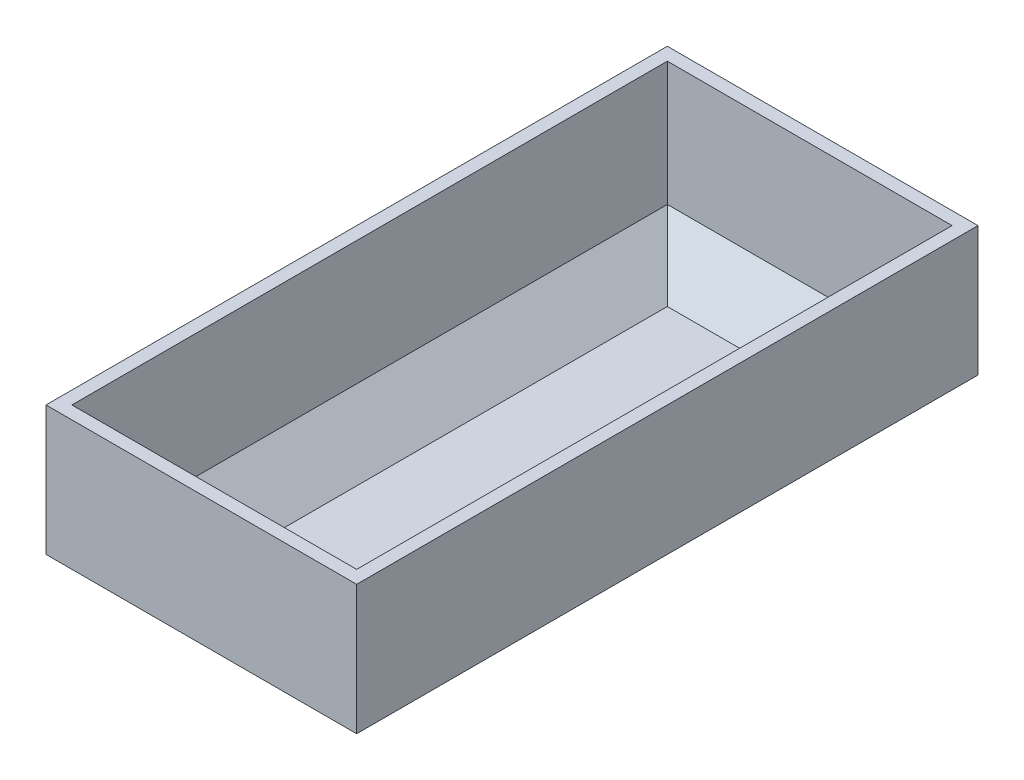
SolidWorks part; units mm, degrees
ref_plane "Frontal Plane" through (0, 0, 0) normal (0, 0, 1) x (1, 0, 0)
ref_plane "Horizontal Plane" through (0, 0, 0) normal (0, 1, 0) x (1, 0, 0)
ref_plane "Profile Plane" through (0, 0, 0) normal (1, 0, 0) x (0, 0, -1)
sketch "Sketch1" plane through (0, 0, 0) normal (0, 0, 1) x (1, 0, 0)
  line L0 (-101.6, 0) -> (101.6, 0)
  line L1 (-101.6, 0) -> (-152.4, 50.8)
  line L2 (-152.4, 50.8) -> (-152.4, 177.8)
  line L3 (-152.4, 177.8) -> (152.4, 177.8)
  line L4 (152.4, 177.8) -> (152.4, 50.8)
  line L5 (152.4, 50.8) -> (101.6, 0)
  point P3 (0, 0)
  dimension "D1" = 304.8
  dimension "D2" = 203.2
  dimension "D3" = 50.8
  dimension "D4" = 127
extrude "Boss-Extrude1" add sketch "Sketch1" along normal mid plane 609.6
sketch "Sketch3" plane through (0, 0, 0) normal (1, 0, 0) x (0, 0, -1)
  line L0 (-304.8, 50.8) -> (-304.8, 0)
  line L1 (-304.8, 50.8) -> (-254, 0)
  line L2 (-304.8, 0) -> (304.8, 0) construction
  line L3 (-304.8, 0) -> (-254, 0)
  line L4 (304.8, 50.8) -> (304.8, 0)
  line L5 (304.8, 0) -> (254, 0)
  line L6 (254, 0) -> (304.8, 50.8)
  dimension "D1" = 45
extrude "Cut-Extrude2" cut sketch "Sketch3" against normal through all both and the other way through all
shell "Shell1" thickness 12.7
